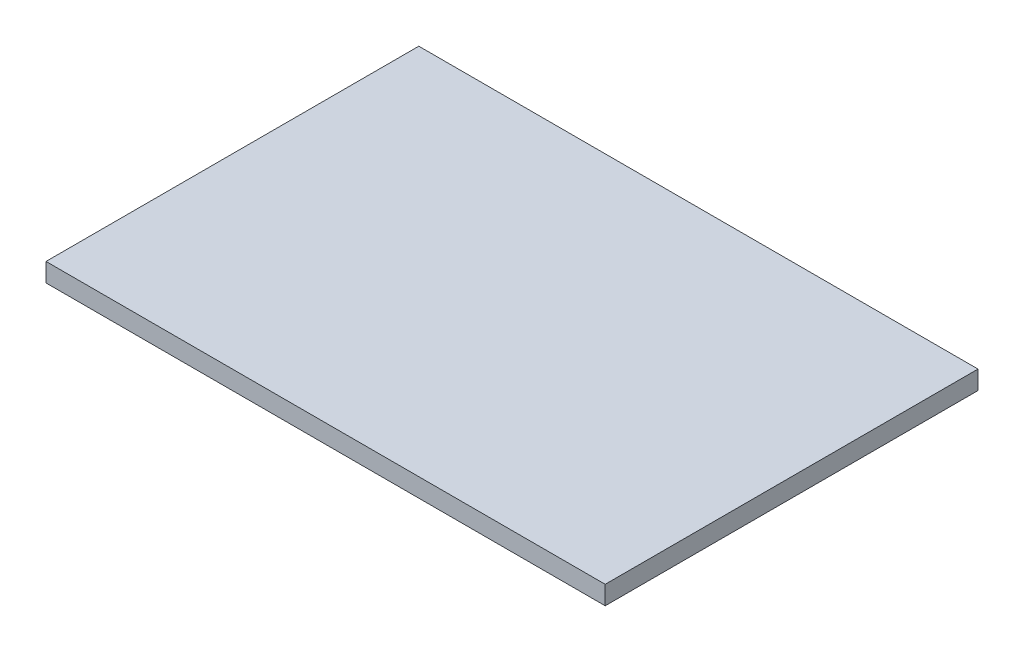
SolidWorks part; units mm, degrees
ref_plane "Front Plane" through (0, 0, 0) normal (0, 0, 1) x (1, 0, 0)
ref_plane "Top Plane" through (0, 0, 0) normal (0, 1, 0) x (1, 0, 0)
ref_plane "Right Plane" through (0, 0, 0) normal (1, 0, 0) x (0, 0, -1)
sketch "Sketch1" plane through (0, 0, 0) normal (0, 1, 0) x (1, 0, 0)
  line L1 (-75, 50) -> (75, 50)
  line L2 (-75, 50) -> (-75, -50)
  line L3 (-75, -50) -> (75, -50)
  line L4 (75, 50) -> (75, -50)
  line L5 (-75, 50) -> (75, -50) construction
  line L6 (-75, -50) -> (75, 50) construction
  point P0 (0, 0)
  dimension "D1" = 150
  dimension "D2" = 100
extrude "Boss-Extrude1" add sketch "Sketch1" along normal blind 5
